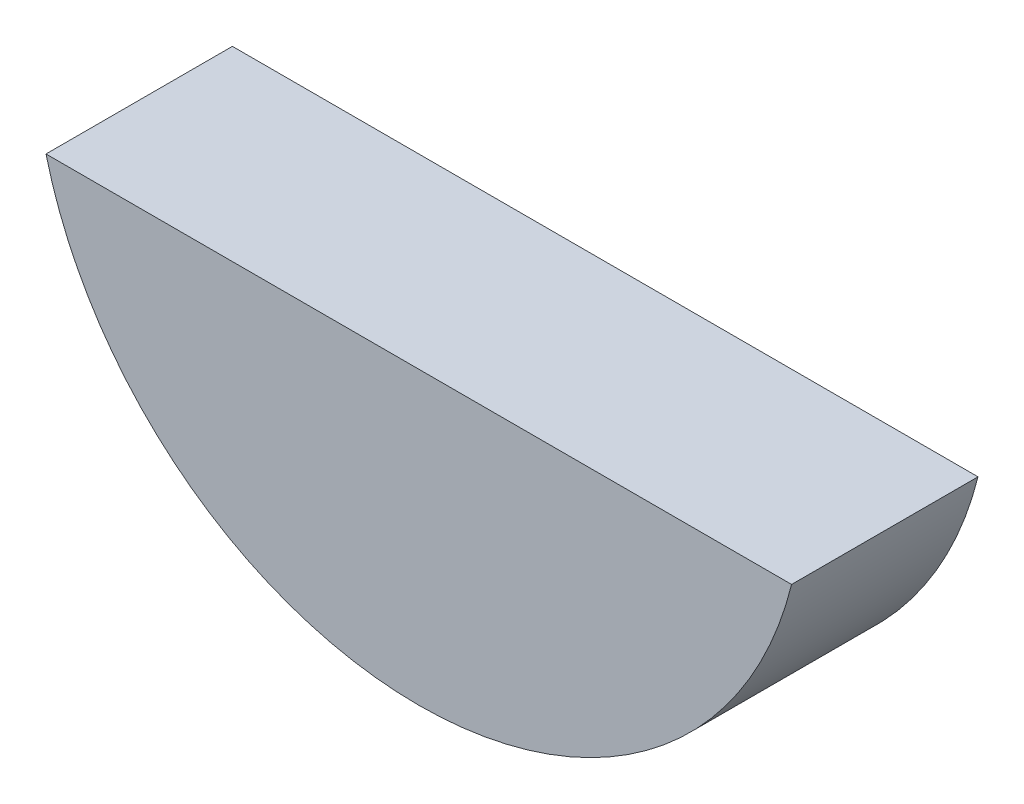
SolidWorks part; units mm, degrees
ref_plane "Front Plane" through (0, 0, 0) normal (0, 0, 1) x (1, 0, 0)
ref_plane "Top Plane" through (0, 0, 0) normal (0, 1, 0) x (1, 0, 0)
ref_plane "Right Plane" through (0, 0, 0) normal (1, 0, 0) x (0, 0, -1)
sketch "Sketch1" plane through (0, 0, 0) normal (0, 0, 1) x (1, 0, 0)
  line L0 (-4, 0) -> (4, 0)
  line L1 (-4, 1) -> (4, 1) construction
  arc A0 (-4, 0) -> (4, 0) centre (0, 1) ccw
  point P4 (0, 0)
extrude "Boss-Extrude1" add sketch "Sketch1" along normal mid plane 2
